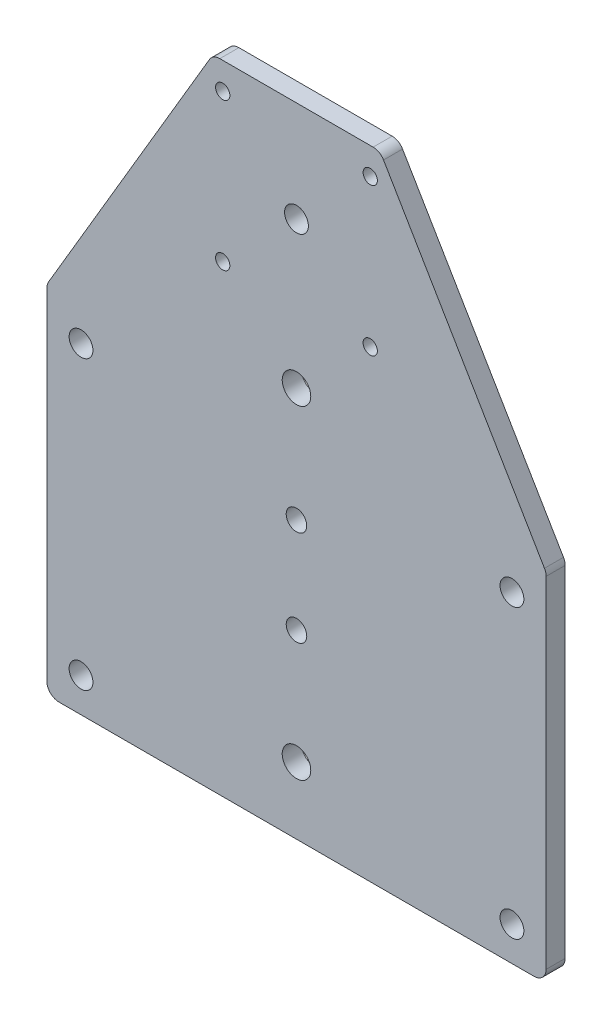
SolidWorks part; units mm, degrees
ref_plane "Front Plane" through (0, 0, 0) normal (0, 0, 1) x (1, 0, 0)
ref_plane "Top Plane" through (0, 0, 0) normal (0, 1, 0) x (1, 0, 0)
ref_plane "Right Plane" through (0, 0, 0) normal (1, 0, 0) x (0, 0, -1)
sketch "Sketch1" plane through (0, 0, 0) normal (0, 0, 1) x (1, 0, 0)
  line L0 (-21.15, 9.85) -> (-9.85, 21.15)
  line L1 (-21.15, -21.15) -> (21.15, -21.15)
  line L2 (-21.15, -21.15) -> (-21.15, 21.15)
  line L3 (-21.15, 21.15) -> (21.15, 21.15)
  line L4 (21.15, -21.15) -> (21.15, 21.15)
  line L5 (-21.15, -21.15) -> (21.15, 21.15) construction
  line L6 (-21.15, 21.15) -> (21.15, -21.15) construction
  line L7 (0, 21.15) -> (0, -21.15) construction
  line L8 (-21.15, 0) -> (21.15, 0) construction
  line L9 (21.15, 9.85) -> (9.85, 21.15)
  line L10 (21.15, -9.85) -> (9.85, -21.15)
  line L11 (-21.15, -9.85) -> (-9.85, -21.15)
  line L12 (-21.15, 17.5579) -> (-17.5579, 21.15)
  line L13 (21.15, 17.5579) -> (17.5579, 21.15)
  line L14 (21.15, -17.5579) -> (17.5579, -21.15)
  line L15 (-21.15, -17.5579) -> (-17.5579, -21.15)
  circle A0 centre (-15.5, 15.5) radius 1.5
  circle A1 centre (15.5, 15.5) radius 1.5
  circle A2 centre (15.5, -15.5) radius 1.5
  circle A3 centre (-15.5, -15.5) radius 1.5
  circle A4 centre (0, 0) radius 2.5
  point P0 (0, 0)
  point P14 (-15.5, 15.5)
  point P15 (15.5, 15.5)
  point P32 (-19.3539, 19.3539)
  dimension "D3" = 3
  dimension "D5" = 5
  dimension "D1" = 42.3
  dimension "D2" = 31
  dimension "D4" = 2.54
sketch "Sketch3" plane through (0, 0, 0) normal (0, 0, 1) x (1, 0, 0)
  line L0 (0, 0) -> (-45.2837, -45.2837) construction
  line L1 (0, 21.15) -> (0, -21.15) construction
  line L2 (0, 21.15) -> (0, -21.15) construction
  line L3 (0, 0) -> (45.2837, -45.2837) construction
  line L4 (-21.15, -21.15) -> (21.15, 21.15) construction
  line L5 (-45.2837, -45.2837) -> (-45.2837, -105.6837) construction
  line L6 (45.2837, -45.2837) -> (45.2837, -105.6837) construction
  line L7 (-45.2837, -75.4837) -> (45.2837, -75.4837) construction
  line L8 (-45.2837, -57.2837) -> (45.2837, -57.2837) construction
  line L9 (-45.2837, -57.2837) -> (0, 21.15) construction
  circle A1 centre (-45.2837, -45.2837) radius 12
  circle A2 centre (45.2837, -45.2837) radius 12
  circle A3 centre (45.2837, -105.6837) radius 12
  circle A4 centre (-45.2837, -105.6837) radius 12
  circle A5 centre (0, 0) radius 4
  circle A6 centre (0, 0) radius 21
  point P19 (-45.2837, -93.6837)
  dimension "D1" = 24
  dimension "D3" = 8
  dimension "D4" = 42
  dimension "D2" = 60.4
  dimension "D5" = 60
sketch "Sketch4" plane through (0, 0, 0) normal (0, 0, 1) x (1, 0, 0)
  line L0 (0, 21.15) -> (0, -21.15) construction
  line L1 (0, 21.15) -> (0, -21.15) construction
  line L2 (-45.2837, -75.4837) -> (45.2837, -75.4837) construction
  line L3 (-45.2837, -75.4837) -> (45.2837, -75.4837) construction
  line L4 (-52.4679, -38.0995) -> (-45.2837, -45.2837)
  line L5 (-52.4679, -38.0995) -> (52.4679, -38.0995)
  line L6 (-52.4679, -38.0995) -> (-52.4679, -112.8679)
  line L7 (-52.4679, -112.8679) -> (52.4679, -112.8679)
  line L8 (52.4679, -38.0995) -> (52.4679, -112.8679)
  line L9 (-45.2837, -45.2837) -> (-52.4679, -45.2837) construction
  line L10 (52.4679, -38.0995) -> (45.2837, -45.2837)
  line L11 (52.4679, -112.8679) -> (45.2837, -105.6837)
  line L12 (-52.4679, -112.8679) -> (-45.2837, -105.6837)
  line L13 (-52.4679, -38.0995) -> (-17.5579, 21.15)
  line L14 (-17.5579, 21.15) -> (17.5579, 21.15)
  line L15 (17.5579, 21.15) -> (52.4679, -38.0995)
  circle A0 centre (-45.2837, -45.2837) radius 2.5
  circle A1 centre (45.2837, -45.2837) radius 2.5
  circle A2 centre (45.2837, -105.6837) radius 2.5
  circle A3 centre (-45.2837, -105.6837) radius 2.5
  circle A4 centre (-15.5, -15.5) radius 1.5 construction
  circle A5 centre (-15.5, -15.5) radius 1.5
  circle A6 centre (-15.5, 15.5) radius 1.5 construction
  circle A7 centre (-15.5, 15.5) radius 1.5
  circle A8 centre (15.5, 15.5) radius 1.5 construction
  circle A9 centre (15.5, 15.5) radius 1.5
  circle A10 centre (15.5, -15.5) radius 1.5 construction
  circle A11 centre (15.5, -15.5) radius 1.5
  circle A12 centre (0, 0) radius 2.5 construction
  circle A13 centre (0, 0) radius 2.5
  dimension "D1" = 5
  dimension "D2" = 45
  dimension "D3" = 10.16
extrude "Boss-Extrude1" add sketch "Sketch4" along normal blind 4
sketch "Sketch5" plane through (0, 0, 4) normal (0, 0, 1) x (1, 0, 0)
  line L0 (0, -74.8337) -> (0, -98.8337) construction
  line L3 (0, -74.8337) -> (0, -54.7677)
  line L4 (0, -54.7677) -> (0, -30.7677) construction
  circle A0 centre (-45.2837, -45.2837) radius 2.5 construction
  circle A1 centre (-45.2837, -45.2837) radius 2.5
  circle A2 centre (45.2837, -45.2837) radius 2.5 construction
  circle A3 centre (45.2837, -45.2837) radius 2.5
  circle A4 centre (-45.2837, -105.6837) radius 2.5 construction
  circle A5 centre (-45.2837, -105.6837) radius 2.5
  circle A6 centre (45.2837, -105.6837) radius 2.5 construction
  circle A7 centre (45.2837, -105.6837) radius 2.5
  circle A9 centre (0, -54.7677) radius 2.159
  circle A10 centre (0, -74.8337) radius 2.159
  circle A11 centre (0, -30.7677) radius 3
  circle A12 centre (0, -98.8337) radius 3
  point P12 (0, -101.8337)
  point P19 (0, -64.8007)
  point P25 (-45.2837, -108.1837)
  dimension "D1" = 60.4
  dimension "D2" = 4.318
  dimension "D4" = 6
  dimension "D3" = 20.066
  dimension "D5" = 24
  dimension "D6" = 24
  dimension "D7" = 6.35
extrude "Cut-Extrude1" cut sketch "Sketch5" against normal up to surface (4 mm away) up to face at (-42.7837, -105.6837, 0)
fillet "Fillet1" radius 2.54 6 edges at (-52.4679, -38.0995, 2) (-52.4679, -112.8679, 2) (52.4679, -112.8679, 2) (52.4679, -38.0995, 2) (17.5579, 21.15, 2) (-17.5579, 21.15, 2)
sketch "Sketch7" [suppressed] plane through (0, 0, 4) normal (0, 0, 1) x (1, 0, 0)
  circle A0 centre (0, -105.1658) radius 3 construction
  circle A1 centre (0, -37.0998) radius 3 construction
  circle A2 centre (0, -105.1658) radius 3
  circle A3 centre (0, -37.0998) radius 3
  circle A4 centre (0, -37.0998) radius 2.5
  circle A5 centre (0, -105.1658) radius 2.5
  dimension "D1" = 5
  dimension "D2" = 5
extrude "Boss-Extrude2" [suppressed] add sketch "Sketch7" against normal up to surface (4 mm away)
ref_plane "Plane2" through (0, -75.4837, 0) normal (0, 1, 0) x (1, 0, 0)
